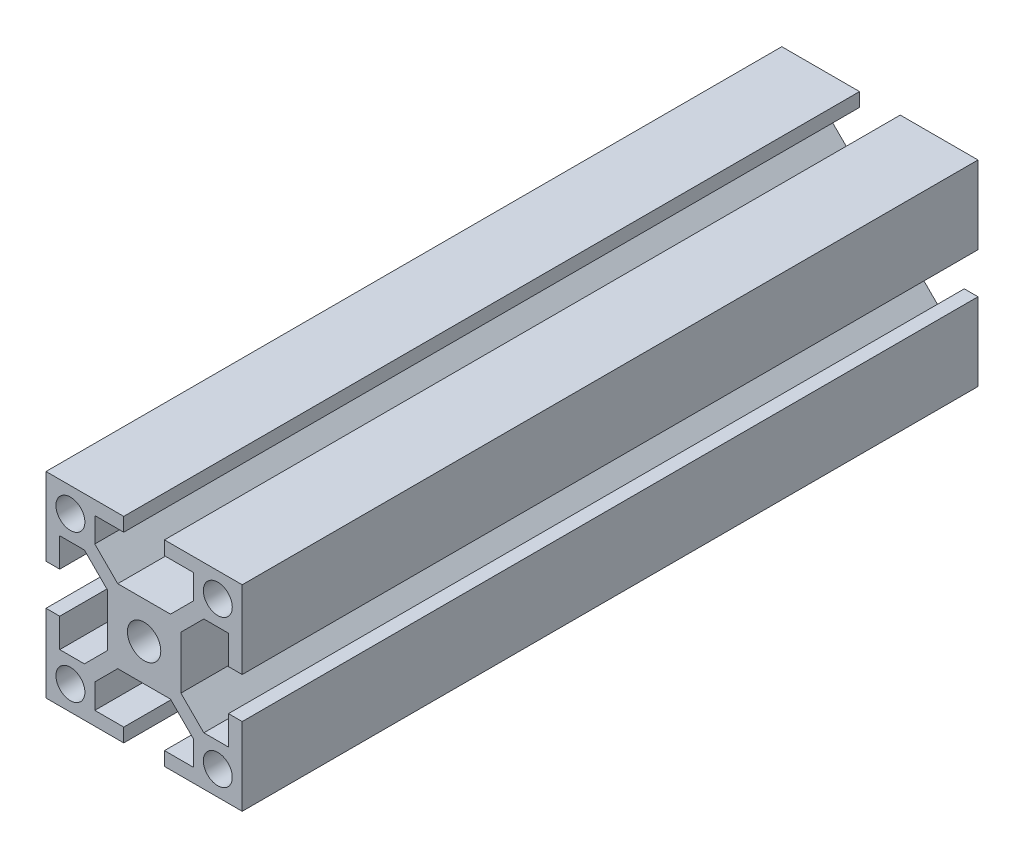
SolidWorks part; units mm, degrees
ref_plane "前视基准面" through (0, 0, 0) normal (0, 0, 1) x (1, 0, 0)
ref_plane "上视基准面" through (0, 0, 0) normal (0, 1, 0) x (1, 0, 0)
ref_plane "右视基准面" through (0, 0, 0) normal (1, 0, 0) x (0, 0, -1)
sketch "草图1" plane through (0, 0, 0) normal (0, 0, 1) x (1, 0, 0)
  line L0 (-8.5791, -8.5791) -> (28.5791, 28.5791) construction
  line L1 (-13.9578, -16.0791) -> (-3.2004, -16.0791)
  line L2 (-16.0791, -13.9578) -> (-16.0791, -3.2004)
  line L3 (-13.9578, -1.0791) -> (-3.2004, -1.0791)
  line L4 (-1.0791, -13.9578) -> (-1.0791, -3.2004)
  line L5 (-16.0791, -16.0791) -> (-1.0791, -1.0791) construction
  line L6 (-16.0791, -1.0791) -> (-1.0791, -16.0791) construction
  line L7 (-1.0791, -3.2004) -> (3.5922, 1.4709)
  line L8 (11.4209, 11.4209) -> (11.4209, -4.4291)
  line L9 (11.4209, 11.4209) -> (-4.4291, 11.4209)
  line L10 (11.4209, -4.4291) -> (8.6209, -4.4291)
  line L11 (-4.4291, 11.4209) -> (-4.4291, 8.6209)
  line L12 (8.6209, -4.4291) -> (8.6209, 1.4709)
  line L13 (3.5922, 1.4709) -> (8.6209, 1.4709)
  line L14 (-4.4291, 8.6209) -> (1.4709, 8.6209)
  line L15 (1.4709, 3.5922) -> (1.4709, 8.6209)
  line L16 (-3.2004, -1.0791) -> (1.4709, 3.5922)
  line L17 (-13.9578, -1.0791) -> (-18.6291, 3.5922)
  line L18 (-18.6291, 3.5922) -> (-18.6291, 8.6209)
  line L19 (-12.7291, 8.6209) -> (-18.6291, 8.6209)
  line L20 (-20.7504, 1.4709) -> (-25.7791, 1.4709)
  line L21 (-25.7791, -4.4291) -> (-25.7791, 1.4709)
  line L22 (-12.7291, 11.4209) -> (-12.7291, 8.6209)
  line L23 (-28.5791, -4.4291) -> (-25.7791, -4.4291)
  line L24 (-28.5791, 11.4209) -> (-12.7291, 11.4209)
  line L25 (-28.5791, 11.4209) -> (-28.5791, -4.4291)
  line L26 (-16.0791, -3.2004) -> (-20.7504, 1.4709)
  line L27 (-16.0791, -13.9578) -> (-20.7504, -18.6291)
  line L28 (-28.5791, -28.5791) -> (-28.5791, -12.7291)
  line L29 (-28.5791, -28.5791) -> (-12.7291, -28.5791)
  line L30 (-28.5791, -12.7291) -> (-25.7791, -12.7291)
  line L31 (-12.7291, -28.5791) -> (-12.7291, -25.7791)
  line L32 (-25.7791, -12.7291) -> (-25.7791, -18.6291)
  line L33 (-20.7504, -18.6291) -> (-25.7791, -18.6291)
  line L34 (-12.7291, -25.7791) -> (-18.6291, -25.7791)
  line L35 (-18.6291, -20.7504) -> (-18.6291, -25.7791)
  line L36 (-13.9578, -16.0791) -> (-18.6291, -20.7504)
  line L37 (-3.2004, -16.0791) -> (1.4709, -20.7504)
  line L38 (1.4709, -20.7504) -> (1.4709, -25.7791)
  line L39 (-4.4291, -25.7791) -> (1.4709, -25.7791)
  line L40 (3.5922, -18.6291) -> (8.6209, -18.6291)
  line L41 (8.6209, -12.7291) -> (8.6209, -18.6291)
  line L42 (-4.4291, -28.5791) -> (-4.4291, -25.7791)
  line L43 (11.4209, -12.7291) -> (8.6209, -12.7291)
  line L44 (11.4209, -28.5791) -> (-4.4291, -28.5791)
  line L45 (11.4209, -28.5791) -> (11.4209, -12.7291)
  line L46 (-1.0791, -13.9578) -> (3.5922, -18.6291)
  circle A0 centre (-8.5791, -8.5791) radius 3.4
  circle A1 centre (6.4459, 6.4459) radius 2.95
  circle A2 centre (-23.6041, 6.4459) radius 2.95
  circle A3 centre (-23.6041, -23.6041) radius 2.95
  circle A4 centre (6.4459, -23.6041) radius 2.95
  dimension "D1" = 6.8
  dimension "D4" = 5.9
  dimension "D2" = 15
  dimension "D3" = 15
  dimension "D5" = 2.8
  dimension "D6" = 7.5
  dimension "D7" = 3
extrude "凸台-拉伸1" add sketch "草图1" along normal blind 150
